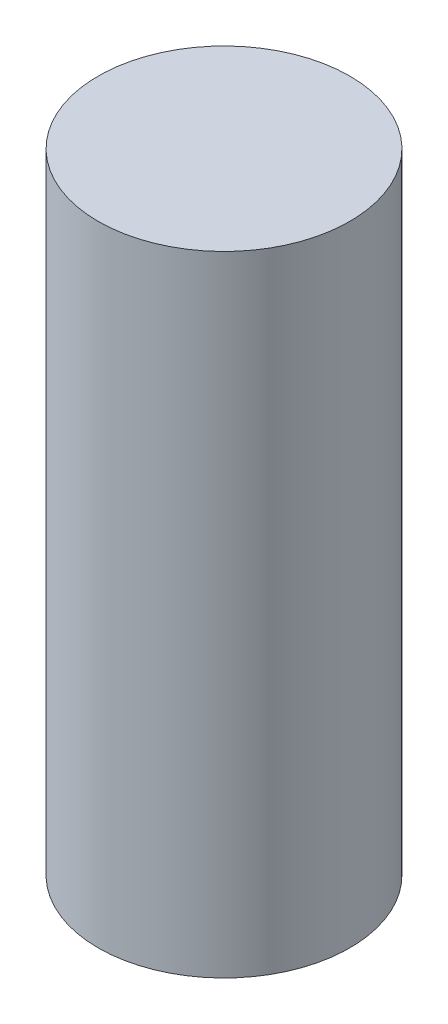
SolidWorks part; units mm, degrees
ref_plane "정면" through (0, 0, 0) normal (0, 0, 1) x (1, 0, 0)
ref_plane "윗면" through (0, 0, 0) normal (0, 1, 0) x (1, 0, 0)
ref_plane "우측면" through (0, 0, 0) normal (1, 0, 0) x (0, 0, -1)
sketch "스케치1" plane through (0, 0, 0) normal (0, 1, 0) x (1, 0, 0)
  circle A0 centre (0, 0) radius 5
  dimension "D1" = 10
extrude "보스-돌출1" add sketch "스케치1" along normal blind 25
